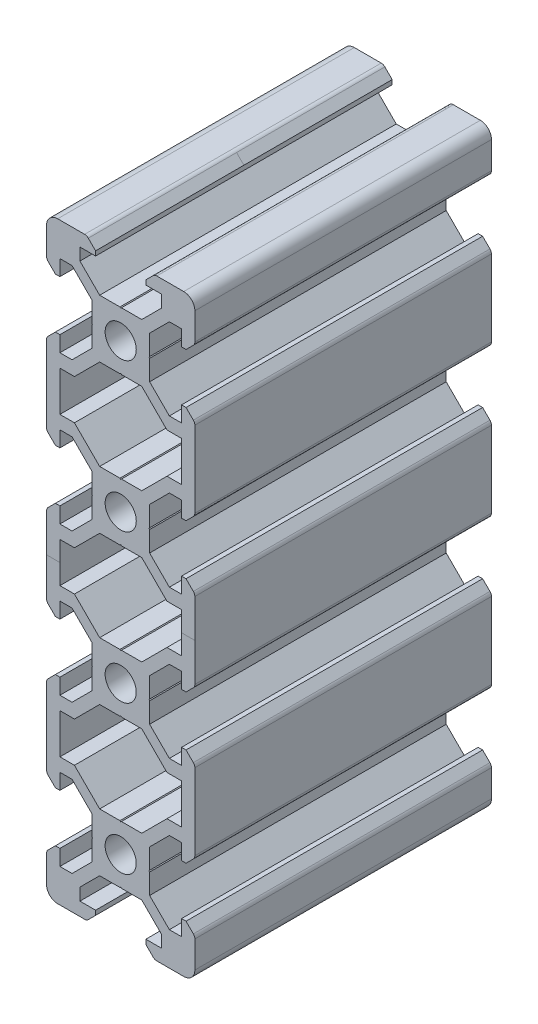
SolidWorks part; units mm, degrees
material "6063-T5"
ref_plane "Front" through (0, 0, 0) normal (0, 0, 1) x (1, 0, 0)
ref_plane "Top" through (0, 0, 0) normal (0, 1, 0) x (1, 0, 0)
ref_plane "Right" through (0, 0, 0) normal (1, 0, 0) x (0, 0, -1)
sketch "Sketch1" plane through (0, 0, 0) normal (0, 0, 1) x (1, 0, 0)
  line L0 (-8.5, 10) -> (-10, 8.5) construction
  line L1 (-8.5, 10) -> (-4.8628, 10)
  line L2 (-10, 8.5) -> (-10, 4.8628)
  line L3 (25.9287, -20) -> (-28.3599, -20) construction
  line L4 (10, 8.5) -> (10, 4.8628)
  line L5 (-10, 10) -> (10, -10) construction
  line L6 (-10, -10) -> (10, 10) construction
  line L7 (8.2, -5.5) -> (8.2, -3.3865)
  line L8 (-8.2, -5.5) -> (-8.2, -3.3865)
  line L9 (-5.5, 8.2) -> (-3.3865, 8.2)
  line L10 (-8.2, -12.7) -> (-8.2, -7.3)
  line L11 (-3.9005, 2.8395) -> (-6.561, 5.5)
  line L12 (-6.561, 5.5) -> (-8.2, 5.5)
  line L13 (-2.8395, -3.9005) -> (-0.1, -3.9005)
  line L14 (-3.9005, -2.8395) -> (-3.9005, -0.1)
  line L15 (-2.8395, 3.9005) -> (-0.1, 3.9005)
  line L16 (3.9005, -2.8395) -> (3.9005, -0.1)
  line L17 (-8.2, 3.3865) -> (-8.81, 3.3865)
  line L18 (-8.81, 3.3865) -> (-9.7976, 4.3741)
  line L19 (8.5, 10) -> (10, 8.5) construction
  line L20 (-2.8395, 3.9005) -> (-5.5, 6.561)
  line L21 (-5.5, 6.561) -> (-5.5, 8.2)
  line L22 (-3.3865, 8.2) -> (-3.3865, 8.81)
  line L23 (-3.3865, 8.81) -> (-4.3741, 9.7976)
  line L24 (0, 24.069) -> (0, -33.8154) construction
  line L25 (3.3865, 8.81) -> (4.3741, 9.7976)
  line L26 (3.3865, 8.2) -> (3.3865, 8.81)
  line L27 (5.5, 6.561) -> (5.5, 8.2)
  line L28 (2.8395, 3.9005) -> (5.5, 6.561)
  line L29 (3.3865, 8.2) -> (5.5, 8.2)
  line L30 (4.8628, 10) -> (8.5, 10)
  line L31 (-0.1, 3.9005) -> (0, 3.8005)
  line L32 (0.1, 3.9005) -> (0, 3.8005)
  line L33 (0.1, 3.9005) -> (2.8395, 3.9005)
  line L34 (25.9287, 0) -> (-28.3459, 0) construction
  line L35 (-0.1, -3.9005) -> (0, -3.8005)
  line L36 (0.1, -3.9005) -> (0, -3.8005)
  line L37 (0.1, -3.9005) -> (2.8395, -3.9005)
  line L38 (-3.9005, 0.1) -> (-3.8005, 0)
  line L39 (-3.8005, 0) -> (-3.9005, -0.1)
  line L40 (-3.9005, 0.1) -> (-3.9005, 2.8395)
  line L41 (3.9005, 0.1) -> (3.8005, 0)
  line L42 (3.8005, 0) -> (3.9005, -0.1)
  line L43 (3.9005, 0.1) -> (3.9005, 2.8395)
  line L44 (8.81, 3.3865) -> (9.7976, 4.3741)
  line L45 (8.2, 3.3865) -> (8.81, 3.3865)
  line L46 (6.561, 5.5) -> (8.2, 5.5)
  line L47 (3.9005, 2.8395) -> (6.561, 5.5)
  line L48 (2.8395, -3.9005) -> (5.5, -6.561)
  line L49 (3.9005, -2.8395) -> (6.561, -5.5)
  line L50 (-2.8395, -3.9005) -> (-5.5, -6.561)
  line L51 (-3.9005, -2.8395) -> (-6.561, -5.5)
  line L52 (6.561, -5.5) -> (8.2, -5.5)
  line L53 (-6.561, -5.5) -> (-8.2, -5.5)
  line L54 (-8.81, -3.3865) -> (-9.7976, -4.3741)
  line L55 (-8.2, -3.3865) -> (-8.81, -3.3865)
  line L56 (8.81, -3.3865) -> (9.7976, -4.3741)
  line L57 (8.2, -3.3865) -> (8.81, -3.3865)
  line L58 (8.2, 3.3865) -> (8.2, 5.5)
  line L59 (10, -4.8628) -> (10, -15.1372)
  line L60 (-8.2, 3.3865) -> (-8.2, 5.5)
  line L61 (-10, -4.8628) -> (-10, -15.1372)
  line L62 (-28.3459, -10) -> (-10, -10) construction
  line L63 (-3.9005, -20.1) -> (-3.9005, -22.8395)
  line L64 (-3.9005, -20.1) -> (-3.8005, -20)
  line L65 (-3.8005, -20) -> (-3.9005, -19.9)
  line L66 (3.9005, -20.1) -> (3.9005, -22.8395)
  line L67 (3.9005, -20.1) -> (3.8005, -20)
  line L68 (3.8005, -20) -> (3.9005, -19.9)
  line L69 (6.561, -14.5) -> (8.2, -14.5)
  line L70 (3.9005, -17.1605) -> (6.561, -14.5)
  line L71 (3.9005, -17.1605) -> (3.9005, -19.9)
  line L72 (-3.9005, -17.1605) -> (-3.9005, -19.9)
  line L73 (-3.9005, -17.1605) -> (-6.561, -14.5)
  line L74 (-6.561, -14.5) -> (-8.2, -14.5)
  line L75 (-8.2, -16.6135) -> (-8.81, -16.6135)
  line L76 (-8.81, -16.6135) -> (-9.7976, -15.6259)
  line L77 (8.2, -16.6135) -> (8.81, -16.6135)
  line L78 (8.81, -16.6135) -> (9.7976, -15.6259)
  line L79 (-2.8395, -16.0995) -> (-5.5, -13.439)
  line L80 (-2.8395, -16.0995) -> (-0.1, -16.0995)
  line L81 (-0.1, -16.0995) -> (0, -16.1995)
  line L82 (0.1, -16.0995) -> (0, -16.1995)
  line L83 (0.1, -16.0995) -> (2.8395, -16.0995)
  line L84 (2.8395, -16.0995) -> (5.5, -13.439)
  line L85 (-8.2, -16.6135) -> (-8.2, -14.5)
  line L86 (8.2, -16.6135) -> (8.2, -14.5)
  line L87 (2.8395, -23.9005) -> (5.5, -26.561)
  line L88 (-2.8395, -23.9005) -> (-5.5, -26.561)
  line L89 (-0.1, -23.9005) -> (0, -23.8005)
  line L90 (0.1, -23.9005) -> (0, -23.8005)
  line L91 (0.1, -23.9005) -> (2.8395, -23.9005)
  line L92 (-2.8395, -23.9005) -> (-0.1, -23.9005)
  line L93 (-8.2, -23.3865) -> (-8.2, -25.5)
  line L94 (-8.2, -23.3865) -> (-8.81, -23.3865)
  line L95 (-8.81, -23.3865) -> (-9.7976, -24.3741)
  line L96 (8.2, -23.3865) -> (8.2, -25.5)
  line L97 (8.2, -23.3865) -> (8.81, -23.3865)
  line L98 (8.81, -23.3865) -> (9.7976, -24.3741)
  line L99 (8.2, -27.3) -> (8.2, -32.7)
  line L100 (10, -35.1372) -> (10, -24.8628)
  line L101 (-10, -35.1372) -> (-10, -24.8628)
  line L102 (-8.2, -27.3) -> (-8.2, -32.7)
  line L103 (3.9005, -22.8395) -> (6.561, -25.5)
  line L104 (-3.9005, -22.8395) -> (-6.561, -25.5)
  line L105 (6.239, -27.3) -> (8.2, -27.3)
  line L106 (-6.239, -27.3) -> (-8.2, -27.3)
  line L107 (-6.561, -25.5) -> (-8.2, -25.5)
  line L108 (6.561, -25.5) -> (8.2, -25.5)
  line L109 (5.5, -26.561) -> (6.239, -27.3)
  line L110 (-5.5, -26.561) -> (-6.239, -27.3)
  line L111 (8.2, -34.5) -> (8.2, -36.6135)
  line L112 (8.2, -36.6135) -> (8.81, -36.6135)
  line L113 (8.81, -36.6135) -> (9.7976, -35.6259)
  line L114 (-8.2, -34.5) -> (-8.2, -36.6135)
  line L115 (-6.239, -7.3) -> (-8.2, -7.3)
  line L116 (-5.5, -6.561) -> (-6.239, -7.3)
  line L117 (6.239, -7.3) -> (8.2, -7.3)
  line L118 (5.5, -6.561) -> (6.239, -7.3)
  line L119 (-6.239, -12.7) -> (-8.2, -12.7)
  line L120 (-5.5, -13.439) -> (-6.239, -12.7)
  line L121 (5.5, -13.439) -> (6.239, -12.7)
  line L122 (6.239, -12.7) -> (8.2, -12.7)
  line L123 (8.2, -12.7) -> (8.2, -7.3)
  line L124 (-8.2, -36.6135) -> (-8.81, -36.6135)
  line L125 (10, -10) -> (25.9287, -10) construction
  line L126 (-8.81, -36.6135) -> (-9.7976, -35.6259)
  line L127 (-0.1, -56.0995) -> (0, -56.1995)
  line L128 (-0.1, -36.0995) -> (0, -36.1995)
  line L129 (0.1, -36.0995) -> (0, -36.1995)
  line L130 (0.1, -36.0995) -> (2.8395, -36.0995)
  line L131 (-6.561, -34.5) -> (-8.2, -34.5)
  line L132 (6.561, -34.5) -> (8.2, -34.5)
  line L133 (6.239, -32.7) -> (8.2, -32.7)
  line L134 (-6.239, -32.7) -> (-8.2, -32.7)
  line L135 (-5.5, -33.439) -> (-6.239, -32.7)
  line L136 (5.5, -33.439) -> (6.239, -32.7)
  line L137 (-26.6965, -30) -> (27.5921, -30) construction
  line L138 (0.1, -56.0995) -> (0, -56.1995)
  line L139 (0.1, -56.0995) -> (2.8395, -56.0995)
  line L140 (-2.8395, -56.0995) -> (-0.1, -56.0995)
  line L141 (0, -60) -> (0, -71.7864) construction
  line L142 (-3.8005, -60) -> (-3.9005, -59.9)
  line L143 (-3.9005, -60.1) -> (-3.8005, -60)
  line L144 (10, -68.5) -> (10, -64.8628)
  line L145 (0.1, -63.9005) -> (0, -63.8005)
  line L146 (-0.1, -63.9005) -> (0, -63.8005)
  line L147 (-2.8395, -63.9005) -> (-0.1, -63.9005)
  line L148 (0.1, -63.9005) -> (2.8395, -63.9005)
  line L149 (3.9005, -60.1) -> (3.9005, -62.8395)
  line L150 (3.9005, -60.1) -> (3.8005, -60)
  line L151 (3.8005, -60) -> (3.9005, -59.9)
  line L152 (3.9005, -57.1605) -> (3.9005, -59.9)
  line L153 (4.8628, -70) -> (8.5, -70)
  line L154 (3.3865, -68.81) -> (4.3741, -69.7976)
  line L155 (3.3865, -68.2) -> (3.3865, -68.81)
  line L156 (3.3865, -68.2) -> (5.5, -68.2)
  line L157 (-0.1, -43.9005) -> (0, -43.8005)
  line L158 (0.1, -43.9005) -> (0, -43.8005)
  line L159 (-2.8395, -43.9005) -> (-0.1, -43.9005)
  line L160 (0.1, -43.9005) -> (2.8395, -43.9005)
  line L161 (3.9005, -40.1) -> (3.8005, -40)
  line L162 (3.8005, -40) -> (3.9005, -39.9)
  line L163 (3.9005, -37.1605) -> (3.9005, -39.9)
  line L164 (3.9005, -40.1) -> (3.9005, -42.8395)
  line L165 (-2.8395, -36.0995) -> (-0.1, -36.0995)
  line L166 (-2.8395, -43.9005) -> (-5.5, -46.561)
  line L167 (-3.9005, -37.1605) -> (-3.9005, -39.9)
  line L168 (-3.8005, -40) -> (-3.9005, -39.9)
  line L169 (-3.9005, -40.1) -> (-3.8005, -40)
  line L170 (-3.9005, -42.8395) -> (-6.561, -45.5)
  line L171 (2.8395, -43.9005) -> (5.5, -46.561)
  line L172 (3.9005, -42.8395) -> (6.561, -45.5)
  line L173 (3.9005, -37.1605) -> (6.561, -34.5)
  line L174 (2.8395, -36.0995) -> (5.5, -33.439)
  line L175 (-3.9005, -42.8395) -> (-3.9005, -40.1)
  line L176 (-6.561, -34.5) -> (-3.9005, -37.1605)
  line L177 (-5.5, -33.439) -> (-2.8395, -36.0995)
  line L178 (5.5, -66.561) -> (5.5, -68.2)
  line L179 (6.561, -65.5) -> (8.2, -65.5)
  line L180 (8.2, -63.3865) -> (8.2, -65.5)
  line L181 (8.81, -63.3865) -> (9.7976, -64.3741)
  line L182 (8.2, -63.3865) -> (8.81, -63.3865)
  line L183 (-8.2, -63.3865) -> (-8.81, -63.3865)
  line L184 (-8.81, -63.3865) -> (-9.7976, -64.3741)
  line L185 (-8.2, -63.3865) -> (-8.2, -65.5)
  line L186 (-6.561, -65.5) -> (-8.2, -65.5)
  line L187 (-5.5, -66.561) -> (-5.5, -68.2)
  line L188 (-5.5, -68.2) -> (-3.3865, -68.2)
  line L189 (-3.3865, -68.2) -> (-3.3865, -68.81)
  line L190 (-3.3865, -68.81) -> (-4.3741, -69.7976)
  line L191 (-10, -68.5) -> (-10, -64.8628)
  line L192 (-8.5, -70) -> (-4.8628, -70)
  line L193 (-8.2, -43.3865) -> (-8.81, -43.3865)
  line L194 (-8.81, -43.3865) -> (-9.7976, -44.3741)
  line L195 (-10, -55.1372) -> (-10, -44.8628)
  line L196 (-8.81, -56.6135) -> (-9.7976, -55.6259)
  line L197 (-8.2, -56.6135) -> (-8.81, -56.6135)
  line L198 (8.2, -56.6135) -> (8.81, -56.6135)
  line L199 (8.81, -56.6135) -> (9.7976, -55.6259)
  line L200 (8.2, -43.3865) -> (8.81, -43.3865)
  line L201 (8.81, -43.3865) -> (9.7976, -44.3741)
  line L202 (10, -55.1372) -> (10, -44.8628)
  line L203 (-8.2, -47.3) -> (-8.2, -52.7)
  line L204 (8.2, -47.3) -> (8.2, -52.7)
  line L205 (-6.239, -52.7) -> (-8.2, -52.7)
  line L206 (6.239, -52.7) -> (8.2, -52.7)
  line L207 (-6.561, -54.5) -> (-8.2, -54.5)
  line L208 (6.561, -54.5) -> (8.2, -54.5)
  line L209 (-3.9005, -60.1) -> (-3.9005, -62.8395)
  line L210 (-2.8395, -56.0995) -> (-5.5, -53.439)
  line L211 (3.9005, -57.1605) -> (6.561, -54.5)
  line L212 (2.8395, -56.0995) -> (5.5, -53.439)
  line L213 (5.5, -53.439) -> (6.239, -52.7)
  line L214 (-5.5, -53.439) -> (-6.239, -52.7)
  line L215 (-8.2, -43.3865) -> (-8.2, -45.5)
  line L216 (8.2, -43.3865) -> (8.2, -45.5)
  line L217 (-2.8395, -63.9005) -> (-5.5, -66.561)
  line L218 (-3.9005, -62.8395) -> (-6.561, -65.5)
  line L219 (2.8395, -63.9005) -> (5.5, -66.561)
  line L220 (3.9005, -62.8395) -> (6.561, -65.5)
  line L221 (-8.2, -54.5) -> (-8.2, -56.6135)
  line L222 (8.2, -54.5) -> (8.2, -56.6135)
  line L223 (6.239, -47.3) -> (8.2, -47.3)
  line L224 (-6.239, -47.3) -> (-8.2, -47.3)
  line L225 (-6.561, -45.5) -> (-8.2, -45.5)
  line L226 (-5.5, -46.561) -> (-6.239, -47.3)
  line L227 (6.561, -45.5) -> (8.2, -45.5)
  line L228 (5.5, -46.561) -> (6.239, -47.3)
  line L229 (-3.9005, -57.1605) -> (-3.9005, -59.9)
  line L230 (-3.9005, -57.1605) -> (-6.561, -54.5)
  circle A0 centre (0, 0) radius 2.1
  arc A1 (-8.5, 10) -> (-10, 8.5) centre (-8.5, 8.5) ccw
  arc A2 (10, 8.5) -> (8.5, 10) centre (8.5, 8.5) ccw
  arc A3 (-4.3741, 9.7976) -> (-4.8628, 10) centre (-4.8628, 9.3088) ccw
  arc A4 (4.8628, 10) -> (4.3741, 9.7976) centre (4.8628, 9.3088) ccw
  circle A5 centre (0, -20) radius 2.1
  arc A6 (9.7976, 4.3741) -> (10, 4.8628) centre (9.3088, 4.8628) ccw
  arc A7 (-10, 4.8628) -> (-9.7976, 4.3741) centre (-9.3088, 4.8628) ccw
  arc A8 (-10, -4.8628) -> (-9.7976, -4.3741) centre (-9.3088, -4.8628) cw
  arc A9 (9.7976, -4.3741) -> (10, -4.8628) centre (9.3088, -4.8628) cw
  arc A10 (-10, -15.1372) -> (-9.7976, -15.6259) centre (-9.3088, -15.1372) ccw
  arc A11 (9.7976, -15.6259) -> (10, -15.1372) centre (9.3088, -15.1372) ccw
  arc A12 (-10, -24.8628) -> (-9.7976, -24.3741) centre (-9.3088, -24.8628) cw
  arc A13 (9.7976, -24.3741) -> (10, -24.8628) centre (9.3088, -24.8628) cw
  arc A14 (9.7976, -35.6259) -> (10, -35.1372) centre (9.3088, -35.1372) ccw
  arc A15 (-10, -35.1372) -> (-9.7976, -35.6259) centre (-9.3088, -35.1372) ccw
  circle A16 centre (0, -40) radius 2.1
  circle A17 centre (0, -60) radius 2.1
  arc A18 (10, -68.5) -> (8.5, -70) centre (8.5, -68.5) cw
  arc A19 (4.8628, -70) -> (4.3741, -69.7976) centre (4.8628, -69.3088) cw
  arc A20 (9.7976, -64.3741) -> (10, -64.8628) centre (9.3088, -64.8628) cw
  arc A21 (-10, -64.8628) -> (-9.7976, -64.3741) centre (-9.3088, -64.8628) cw
  arc A22 (-4.3741, -69.7976) -> (-4.8628, -70) centre (-4.8628, -69.3088) cw
  arc A23 (-8.5, -70) -> (-10, -68.5) centre (-8.5, -68.5) cw
  arc A24 (-10, -44.8628) -> (-9.7976, -44.3741) centre (-9.3088, -44.8628) cw
  arc A25 (-10, -55.1372) -> (-9.7976, -55.6259) centre (-9.3088, -55.1372) ccw
  arc A26 (9.7976, -55.6259) -> (10, -55.1372) centre (9.3088, -55.1372) ccw
  arc A27 (9.7976, -44.3741) -> (10, -44.8628) centre (9.3088, -44.8628) cw
  point P17 (-9.25, 9.25)
  point P21 (9.25, 9.25)
  point P181 (-10, -30)
  dimension "D2" = 4.2
  dimension "D4" = 1.5
  dimension "D3" = 20
  dimension "D5" = 0.529
  dimension "D6" = 6.773
  dimension "D7" = 90
  dimension "D8" = 11
  dimension "D9" = 0.61
  dimension "D10" = 0.1
  dimension "D11" = 0.1
  dimension "D12" = 0.1
  dimension "D13" = 0.1
  dimension "D14" = 5.679
  dimension "D15" = 1.639
  dimension "D16" = 1.8
  dimension "D17" = 90
  dimension "D18" = 6.773
  dimension "D19" = 90
  dimension "D20" = 20
  dimension "D21" = 1.8
extrude "Boss-Extrude2" add sketch "Sketch1" along normal blind 40
sketch "Sketch2" plane through (0, 0, 40) normal (0, 0, 1) x (1, 0, 0)
  line L0 (-10, -30) -> (10, -30)
  line L1 (-10, -24.8628) -> (-10, -35.1372) construction
  line L2 (10, -35.1372) -> (10, -24.8628) construction
split line "SideFixture1 - SplitLine"
sketch "Sketch3" plane through (0, 0, 0) normal (0, 0, -1) x (-1, 0, 0)
  line L0 (-10, -30) -> (10, -30)
  line L1 (-10, -35.1372) -> (-10, -24.8628) construction
  line L2 (10, -24.8628) -> (10, -35.1372) construction
split line "SideFixture2 - SplitLine"
sketch "Sketch4" plane through (0, 10, 0) normal (0, 1, 0) x (1, 0, 0)
  line L0 (8.5, -20) -> (-8.5, -20)
  line L1 (8.5, -40) -> (8.5, 0) construction
  line L2 (-8.5, -40) -> (-8.5, 0) construction
split line "SideFixture3 - SplitLine"
